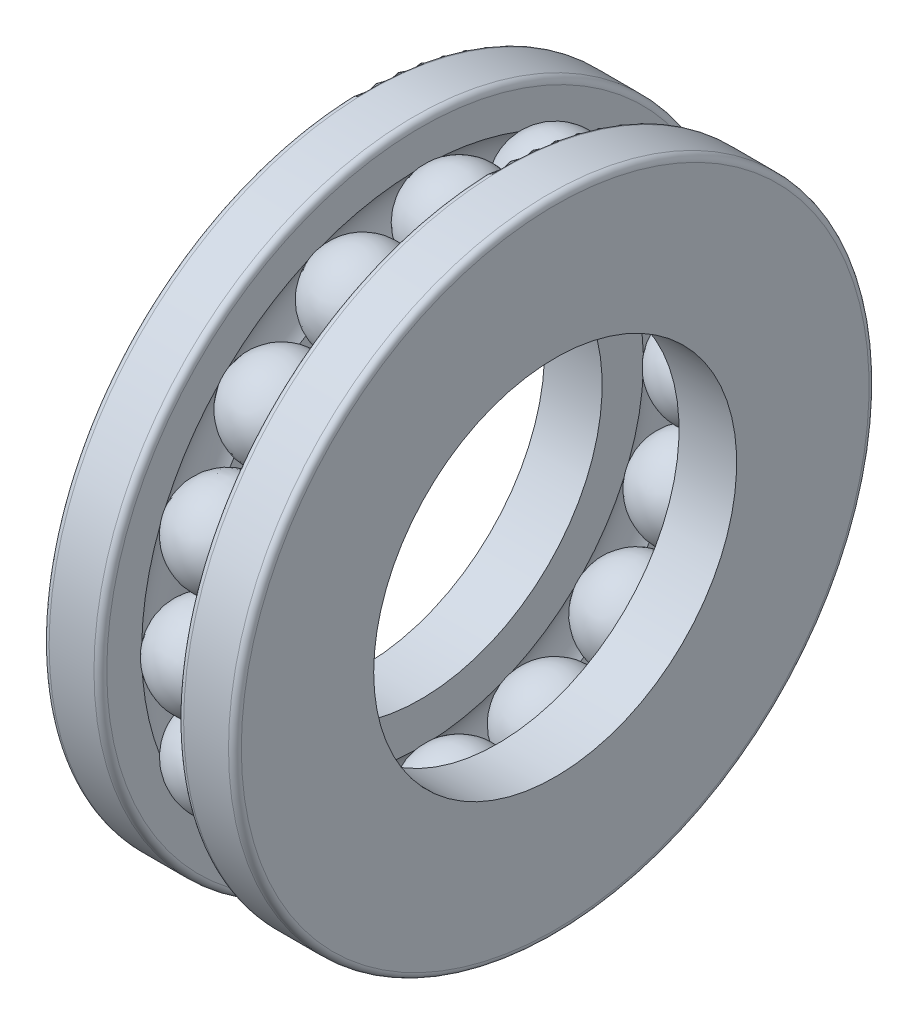
SolidWorks part; units mm, degrees
ref_plane "Front" through (0, 0, 0) normal (0, 0, 1) x (1, 0, 0)
ref_plane "Top" through (0, 0, 0) normal (0, 1, 0) x (1, 0, 0)
ref_plane "Right" through (0, 0, 0) normal (1, 0, 0) x (0, 0, -1)
other "Configuration Table"
sketch "Sketch1" plane through (0, 0, 0) normal (0, 0, 1) x (0, 1, 0)
  line L0 (0, 1.4099) -> (0, -1.5142) construction
  line L1 (9.5, 0) -> (14, 0)
  line L2 (4.3776, 0) -> (11.8663, 0) construction
  line L3 (11.75, 4.5) -> (13.0112, 4.5) construction
  line L4 (11.75, -4.5) -> (13.0112, -4.5) construction
  line L5 (8.5, 0) -> (8.5, 2.3607) construction
  line L6 (-8.5, 0) -> (-8.5, 2.3607) construction
  line L7 (15, 0) -> (15, 3.0588) construction
  line L8 (-15, 0) -> (-15, 3.0588) construction
  arc A0 (9.5, 0) -> (14, 0) centre (11.75, 0) ccw
  dimension "d0" = 4.5
  dimension "dd0" = 23.5
  dimension "T" = 9
  dimension "d" = 17
  dimension "DD" = 30
revolve "Revolve1" add sketch "Sketch1" angle 360 about L2
sketch "Sketch2" plane through (0, 0, 0) normal (0, 0, 1) x (0, 1, 0)
  line L0 (8.5, 4.5) -> (8.5, 1.8)
  line L1 (8.5, 1.8) -> (10.4336, 1.8)
  line L2 (8.5, 4.5) -> (15, 4.5)
  line L3 (15, 4.5) -> (15, 1.8)
  line L4 (15, 1.8) -> (13.0664, 1.8)
  line L5 (0, 4.8736) -> (0, -4.1797) construction
  line L6 (-8.0647, 0) -> (13.4529, 0) construction
  arc A0 (13.0664, 1.8) -> (10.4336, 1.8) centre (11.75, 0) ccw
  circle A1 centre (11.75, 0) radius 2.25 construction
  dimension "T" = 9
  dimension "dd1" = 4.46
  dimension "D" = 30
  dimension "d1" = 17
  dimension "B1/2" = 1.8
revolve "Revolve2" add sketch "Sketch2" angle 360 about L5
sketch "Sketch3" plane through (0, 0, 0) normal (0, 0, 1) x (0, 1, 0)
  line L0 (-2.5215, 0) -> (12.4263, 0) construction
  line L1 (8.5, -1.8) -> (10.4336, -1.8)
  line L2 (8.5, -1.8) -> (8.5, -4.5)
  line L3 (8.5, -4.5) -> (15, -4.5)
  line L4 (15, -1.8) -> (15, -4.5)
  line L5 (0, 8.7259) -> (0, -4.9884) construction
  line L6 (13.0664, -1.8) -> (15, -1.8)
  arc A0 (10.4, 1.8) -> (13.1, 1.8) centre (11.75, 0) ccw construction
  arc A1 (10.4336, -1.8) -> (13.0664, -1.8) centre (11.75, 0) ccw
  dimension "T" = 9
  dimension "d" = 17
  dimension "D1" = 4.46
  dimension "DD1" = 30
  dimension "D2" = 1.8
revolve "Revolve3" add sketch "Sketch3" angle 360 about L5
pattern_circular "Circular-Pattern1" count 16 over 360 about axis through (0, 0, 0) along (1, 0, 0) of "Revolve1"
fillet "Fillet1" radius 0.3 4 edges at (4.5, 0, 15) (1.8, 0, 15) (-1.8, 0, 15) (-4.5, 0, 15)
equation "\"d0@Sketch1\" = \"T@Sketch1\" / 2"
equation "\"dd0@Sketch1\" =  ( \"d@Sketch1\" + \"DD@Sketch1\" )  / 2"
equation "\"T@Sketch2\" = \"T@Sketch1\""
equation "\"dd1@Sketch2\" = \"d0@Sketch1\" - 0.04"
equation "\"B1/2@Sketch2\" = \"T@Sketch2\" / 5"
equation "\"D2@Sketch3\" = \"B1/2@Sketch2\""
equation "\"D1@Sketch3\" = \"dd1@Sketch2\""
equation "\"T@Sketch3\" = \"T@Sketch2\""
equation "\"m@Circular-Pattern1\" = int( 3.14159265 / atn((  \"d0@Sketch1\"/ 2) / sqr( \"dd0@Sketch1\"/2 * \"dd0@Sketch1\"/2 - ( \"d0@Sketch1\"/ 2) *  ( \"d0@Sketch1\" / 2))))"
